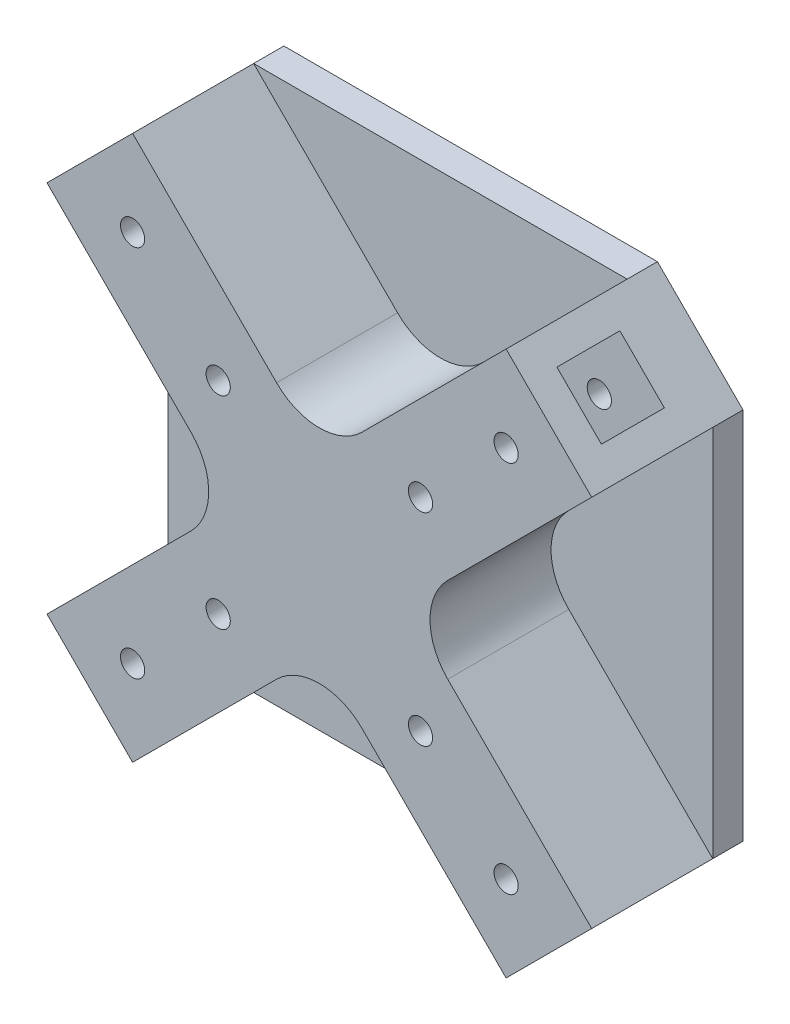
SolidWorks part; units mm, degrees
material "ABS"
ref_plane "Front Plane" through (0, 0, 0) normal (0, 0, 1) x (1, 0, 0)
ref_plane "Top Plane" through (0, 0, 0) normal (0, 1, 0) x (1, 0, 0)
ref_plane "Right Plane" through (0, 0, 0) normal (1, 0, 0) x (0, 0, -1)
sketch "Sketch1" plane through (0, 0, 0) normal (0, 0, 1) x (1, 0, 0)
  line L0 (-28.575, 19.5947) -> (-19.5947, 28.575)
  line L1 (-28.575, -28.575) -> (28.575, -28.575) construction
  line L2 (-28.575, -28.575) -> (-28.575, 28.575) construction
  line L3 (-28.575, 28.575) -> (28.575, 28.575) construction
  line L4 (28.575, -28.575) -> (28.575, 28.575) construction
  line L5 (-28.575, -28.575) -> (28.575, 28.575) construction
  line L6 (-28.575, 28.575) -> (28.575, -28.575) construction
  line L7 (-56.4568, 0) -> (75.3413, 0) construction
  line L8 (19.5947, -28.575) -> (28.575, -19.5947)
  line L9 (19.5947, 28.575) -> (28.575, 19.5947)
  line L10 (-28.575, -19.5947) -> (-19.5947, -28.575)
  line L11 (-28.575, 19.5947) -> (-28.575, -19.5947)
  line L12 (-19.5947, -28.575) -> (19.5947, -28.575)
  line L13 (19.5947, 28.575) -> (-19.5947, 28.575)
  line L14 (28.575, 19.5947) -> (28.575, -19.5947)
  point P0 (0, 0)
  dimension "D1" = 57.15
  dimension "D2" = 57.15
  dimension "D3" = 12.7
  dimension "D4" = 45
  dimension "D5" = 39.1895
  dimension "D6" = 39.1895
  dimension "D7" = 45
extrude "Boss-Extrude1" add sketch "Sketch1" along normal blind 3.175
sketch "Sketch2" plane through (0, 0, 3.175) normal (0, 0, 1) x (1, 0, 0)
  line L0 (0, 0) -> (-42.3568, 42.3568) construction
  line L1 (0, 0) -> (-68.2818, 0) construction
  line L2 (0, 0) -> (0, 61.7261) construction
  line L3 (-28.575, 19.5947) -> (-19.5947, 28.575)
  line L4 (-19.5947, 28.575) -> (-4.4901, 13.4704)
  line L5 (-28.575, 19.5947) -> (-13.4704, 4.4901)
  line L6 (-19.5947, -28.575) -> (-4.4901, -13.4704)
  line L7 (-28.575, -19.5947) -> (-19.5947, -28.575)
  line L8 (-28.575, -19.5947) -> (-13.4704, -4.4901)
  line L9 (28.575, -19.5947) -> (13.4704, -4.4901)
  line L10 (28.575, -19.5947) -> (19.5947, -28.575)
  line L11 (19.5947, -28.575) -> (4.4901, -13.4704)
  line L12 (28.575, 19.5947) -> (13.4704, 4.4901)
  line L13 (19.5947, 28.575) -> (4.4901, 13.4704)
  line L14 (28.575, 19.5947) -> (19.5947, 28.575)
  arc A0 (-4.4901, 13.4704) -> (4.4901, 13.4704) centre (0, 17.9605) ccw
  arc A1 (-13.4704, 4.4901) -> (-13.4704, -4.4901) centre (-17.9605, 0) cw
  arc A2 (-4.4901, -13.4704) -> (4.4901, -13.4704) centre (0, -17.9605) cw
  arc A3 (13.4704, 4.4901) -> (13.4704, -4.4901) centre (17.9605, 0) ccw
  dimension "D1" = 6.35
extrude "Boss-Extrude2" add sketch "Sketch2" along normal blind 12.7
sketch "Sketch3" plane through (24.0849, 24.0849, 0) normal (0.7071, 0.7071, 0) x (0, 0, -1)
  line L0 (0, 0) -> (-26.3299, 0) construction
  line L1 (-12.7, -3.302) -> (-6.096, -3.302)
  line L2 (-12.7, -3.302) -> (-12.7, 3.302)
  line L3 (-12.7, 3.302) -> (-6.096, 3.302)
  line L4 (-6.096, -3.302) -> (-6.096, 3.302)
  line L5 (-12.7, -3.302) -> (-6.096, 3.302) construction
  line L6 (-12.7, 3.302) -> (-6.096, -3.302) construction
  line L7 (0, -6.35) -> (0, 6.35) construction
  line L8 (-15.875, -6.35) -> (-15.875, 6.35) construction
  point P0 (-9.398, 0)
  dimension "D1" = 6.604
  dimension "D2" = 6.604
  dimension "D3" = 3.175
extrude "Cut-Extrude1" cut sketch "Sketch3" against normal through all both and the other way through all
mirror "Mirror1" about plane through (0, 0, 0) normal (0, 1, 0) of "Cut-Extrude1"
sketch "Sketch4" plane through (0, 0, 0) normal (0, 0, -1) x (-1, 0, 0)
  line L0 (0, 0) -> (-40.1691, 0) construction
  line L1 (0, 0) -> (0, 39.2686) construction
  line L2 (0, 0) -> (-36.3863, 36.3863) construction
  line L3 (-28.575, 19.5947) -> (-19.5947, 28.575) construction
  circle A0 centre (-19.5947, 19.5947) radius 1.27
  circle A1 centre (-10.6145, 10.6145) radius 1.27
  circle A2 centre (10.6145, 10.6145) radius 1.27
  circle A3 centre (19.5947, 19.5947) radius 1.27
  circle A4 centre (19.5947, -19.5947) radius 1.27
  circle A5 centre (10.6145, -10.6145) radius 1.27
  circle A6 centre (-19.5947, -19.5947) radius 1.27
  circle A7 centre (-10.6145, -10.6145) radius 1.27
  dimension "D1" = 2.54
  dimension "D2" = 2.54
  dimension "D3" = 12.7
  dimension "D4" = 6.35
extrude "Cut-Extrude3" cut sketch "Sketch4" against normal blind 25.4
